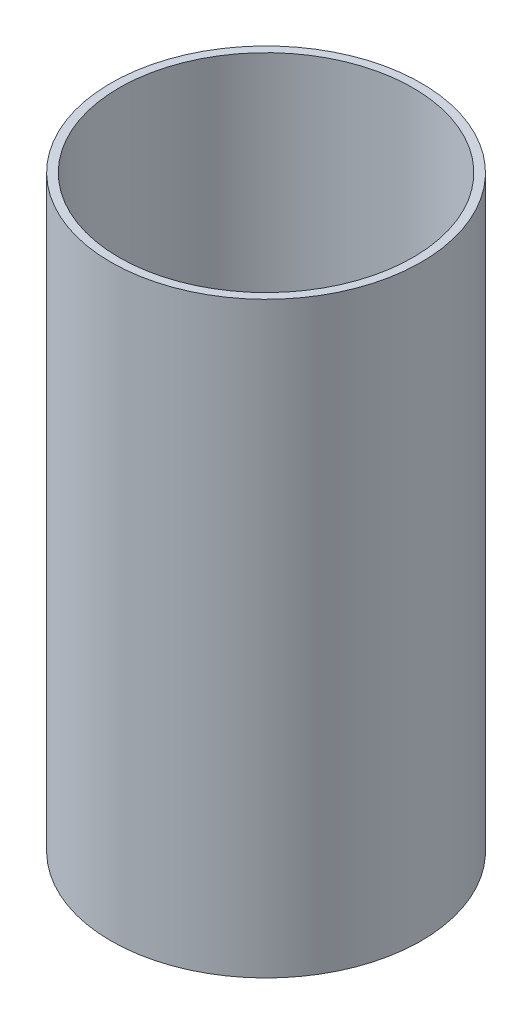
SolidWorks part; units mm, degrees
ref_plane "Front Plane" through (0, 0, 0) normal (0, 0, 1) x (1, 0, 0)
ref_plane "Top Plane" through (0, 0, 0) normal (0, 1, 0) x (1, 0, 0)
ref_plane "Right Plane" through (0, 0, 0) normal (1, 0, 0) x (0, 0, -1)
sketch "Sketch1" plane through (0, 0, 0) normal (0, 1, 0) x (1, 0, 0)
  circle A0 centre (0, 0) radius 31.75
  circle A1 centre (0, 0) radius 33.528
  dimension "D1" = 63.5
  dimension "D2" = 1.778
extrude "Boss-Extrude1" add sketch "Sketch1" along normal blind 127
